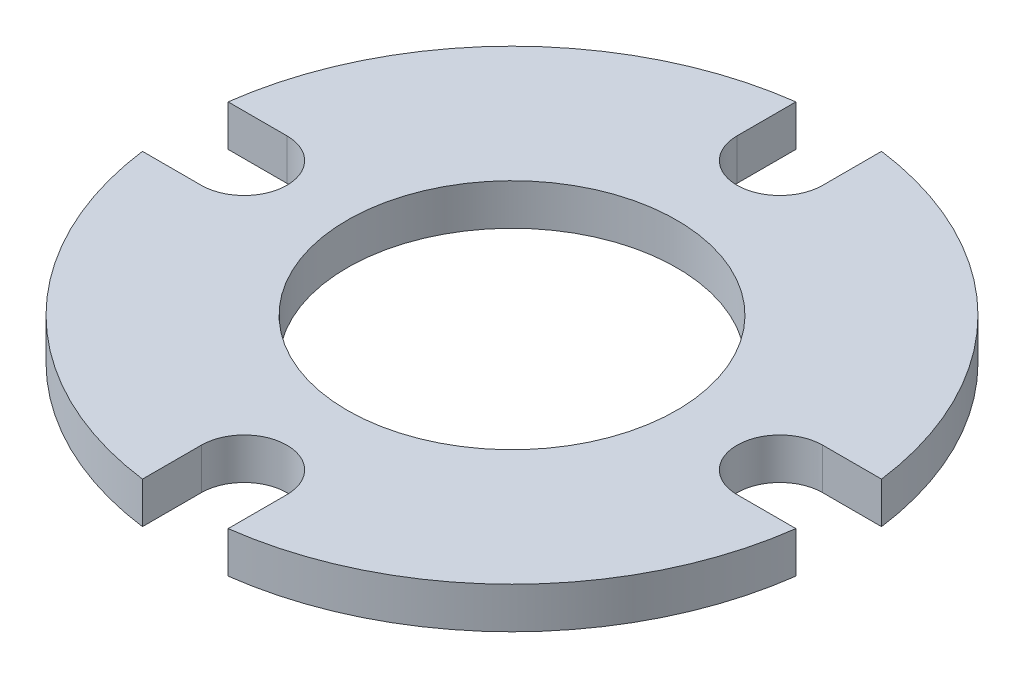
SolidWorks part; units mm, degrees
ref_plane "Front Plane" through (0, 0, 0) normal (0, 0, 1) x (1, 0, 0)
ref_plane "Top Plane" through (0, 0, 0) normal (0, 1, 0) x (1, 0, 0)
ref_plane "Right Plane" through (0, 0, 0) normal (1, 0, 0) x (0, 0, -1)
sketch "Sketch1" plane through (0, 0, 0) normal (0, 1, 0) x (1, 0, 0)
  line L0 (0, 1.4988) -> (0, -1.444) construction
  line L1 (-1.287, 0) -> (1.1159, 0) construction
  line L2 (-1, 0) -> (-0.813, 0) construction
  line L3 (-0.9915, 0.13) -> (-0.813, 0.13)
  line L4 (-0.9915, -0.13) -> (-0.813, -0.13)
  line L5 (0, 1) -> (0, 0.813) construction
  line L6 (0.13, 0.9915) -> (0.13, 0.813)
  line L7 (-0.13, 0.9915) -> (-0.13, 0.813)
  line L8 (0.9915, -0.13) -> (0.813, -0.13)
  line L9 (0.9915, 0.13) -> (0.813, 0.13)
  line L10 (-0.13, -0.9915) -> (-0.13, -0.813)
  line L11 (0.13, -0.9915) -> (0.13, -0.813)
  arc A1 (-0.13, 0.9915) -> (-0.9915, 0.13) centre (0, 0) ccw
  circle A2 centre (0, 0) radius 0.5
  arc A4 (-0.813, -0.13) -> (-0.813, 0.13) centre (-0.813, 0) ccw
  arc A6 (-0.13, 0.813) -> (0.13, 0.813) centre (0, 0.813) ccw
  arc A7 (-0.9915, -0.13) -> (-0.13, -0.9915) centre (0, 0) ccw
  arc A8 (0.813, -0.13) -> (0.813, 0.13) centre (0.813, 0) cw
  arc A9 (-0.13, -0.813) -> (0.13, -0.813) centre (0, -0.813) cw
  arc A10 (0.13, -0.9915) -> (0.9915, -0.13) centre (0, 0) ccw
  arc A11 (0.9915, 0.13) -> (0.13, 0.9915) centre (0, 0) ccw
  point P10 (-0.9065, 0)
  point P15 (0, 0.9065)
  point P20 (0, 0)
  point P25 (0, 0)
  point P26 (0, 0)
  point P27 (0, 0)
  point P28 (0, 0)
  point P32 (0, 0)
  point P33 (0, 0)
  point P34 (0, 0)
  point P36 (0, 0)
  dimension "D1" = 1
  dimension "D2" = 2
  dimension "D5" = 0.13
  dimension "D6" = 0.13
  dimension "D3" = 0.813
  dimension "D4" = 0.813
extrude "Boss-Extrude1" add sketch "Sketch1" along normal blind 0.125
